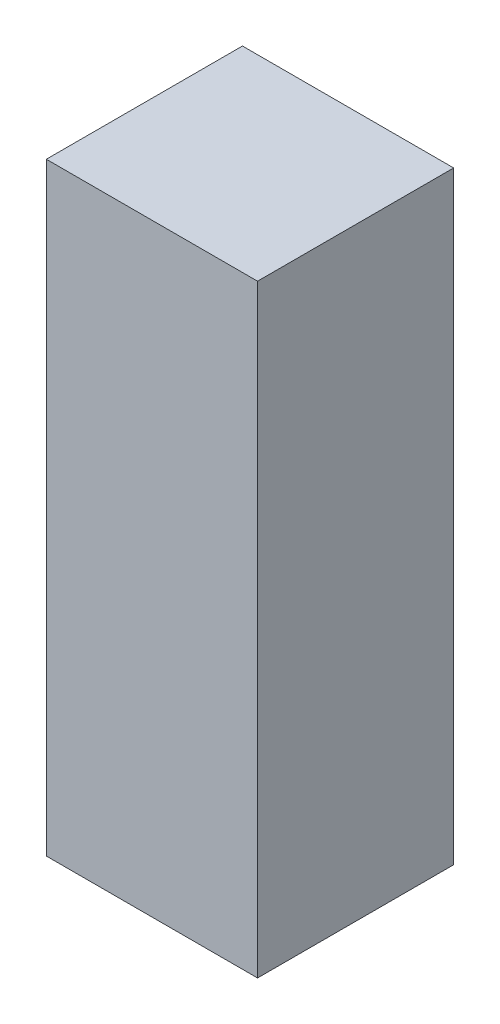
SolidWorks part; units mm, degrees
ref_plane "Front Plane" through (0, 0, 0) normal (0, 0, 1) x (1, 0, 0)
ref_plane "Top Plane" through (0, 0, 0) normal (0, 1, 0) x (1, 0, 0)
ref_plane "Right Plane" through (0, 0, 0) normal (1, 0, 0) x (0, 0, -1)
other "Configuration Table"
sketch "Sketch1" plane through (0, 0, 0) normal (0, 0, 1) x (1, 0, 0)
  line L1 (24, 160) -> (38, 160)
  line L2 (24, 160) -> (24, 200)
  line L3 (24, 200) -> (38, 200)
  line L4 (38, 160) -> (38, 200)
extrude "PACK_pano_kapagi_mentese_1_1" add sketch "Sketch1" along normal blind 13 from offset 20 separate body
